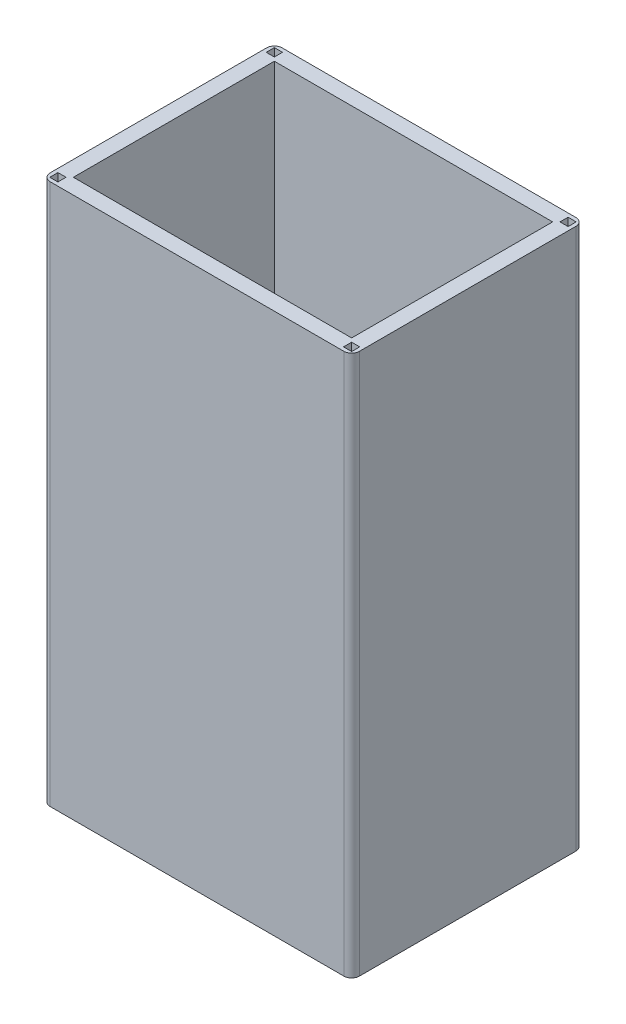
SolidWorks part; units mm, degrees
ref_plane "前视基准面" through (0, 0, 0) normal (0, 0, 1) x (1, 0, 0)
ref_plane "上视基准面" through (0, 0, 0) normal (0, 1, 0) x (1, 0, 0)
ref_plane "右视基准面" through (0, 0, 0) normal (1, 0, 0) x (0, 0, -1)
other "Configuration Table"
sketch "Sketch1" plane through (0, 0, 0) normal (0, 1, 0) x (1, 0, 0)
  line L1 (-50.8, 38.1) -> (50.8, 38.1)
  line L2 (-50.8, 38.1) -> (-50.8, -38.1)
  line L3 (-50.8, -38.1) -> (50.8, -38.1)
  line L4 (50.8, 38.1) -> (50.8, -38.1)
  line L5 (0, -38.1) -> (0, 38.1) construction
  line L6 (-50.8, 0) -> (50.8, 0) construction
  point P0 (0, 0)
  dimension "D1" = 76.2
  dimension "D2" = 101.6
extrude "Boss-Extrude1" add sketch "Sketch1" along normal blind 177.8
shell "Shell1" thickness 5.08
sketch "Sketch2" plane through (0, 177.8, 0) normal (0, 1, 0) x (1, 0, 0)
  line L1 (-49.5935, 36.8935) -> (-46.9265, 36.8935)
  line L2 (-49.5935, 36.8935) -> (-49.5935, 34.2265)
  line L3 (-49.5935, 34.2265) -> (-46.9265, 34.2265)
  line L4 (-46.9265, 36.8935) -> (-46.9265, 34.2265)
  line L5 (-48.26, 34.2265) -> (-48.26, 36.8935) construction
  line L6 (-49.5935, 35.56) -> (-46.9265, 35.56) construction
  line L10 (-50.8, 38.1) -> (-50.8, -38.1) construction
  line L11 (50.8, 38.1) -> (-50.8, 38.1) construction
  point P0 (-48.26, 35.56)
  point P4 (0, 0)
  point P8 (-50.8, 35.0133)
  point P9 (-45.72, 32.2325)
  dimension "D1" = 2.54
  dimension "D2" = 2.54
  dimension "D3" = 2.667
  dimension "D4" = 2.667
extrude "Cut-Extrude1" cut sketch "Sketch2" against normal blind 15.24 draft 1
mirror "Mirror1" about plane through (0, 0, 0) normal (0, 0, 1) of "Cut-Extrude1"
mirror "Mirror2" about plane through (0, 0, 0) normal (1, 0, 0) of "Mirror1", "Cut-Extrude1"
ref_plane "Plane1" through (0, 88.9, 0) normal (0, 1, 0) x (1, 0, 0)
mirror "Mirror3" about plane through (0, 88.9, 0) normal (0, 1, 0) of "Mirror2", "Cut-Extrude1", "Mirror1"
sketch "Sketch3" plane through (0, 0, 33.02) normal (0, 0, -1) x (-1, 0, 0)
  line L1 (-29.21, 144.78) -> (29.21, 144.78)
  line L2 (-29.21, 144.78) -> (-29.21, 58.42)
  line L3 (-29.21, 58.42) -> (29.21, 58.42)
  line L4 (29.21, 144.78) -> (29.21, 58.42)
  line L5 (0, 58.42) -> (0, 144.78) construction
  line L6 (-29.21, 101.6) -> (29.21, 101.6) construction
  point P0 (0, 101.6)
  point P4 (-4.2891, 114.1181)
  point P5 (1.136, 110.536)
  point P6 (0, 167.135)
  point P7 (-0.9695, 87.8887)
  point P8 (0, 115.1601)
  dimension "D1" = 58.42
  dimension "D2" = 86.36
  dimension "D3" = 101.6
extrude "Extrude-Thin1" add sketch "Sketch3" along normal blind 12.7 thin thin type one direction wall 2.54
sketch "Sketch4" plane through (0, 0, 20.32) normal (0, 0, -1) x (-1, 0, 0)
  line L0 (0, 147.32) -> (0, 55.88)
  line L1 (31.75, 147.32) -> (-31.75, 147.32) construction
  line L2 (-31.75, 55.88) -> (31.75, 55.88) construction
extrude "Cut-Extrude-Thin1" cut sketch "Sketch4" against normal blind 12.7 thin thin type mid plane wall 25.4
fillet "Fillet1" radius 2.54 4 edges at (50.8, 88.9, 38.1) (-50.8, 88.9, 38.1) (50.8, 88.9, -38.1) (-50.8, 88.9, -38.1)
